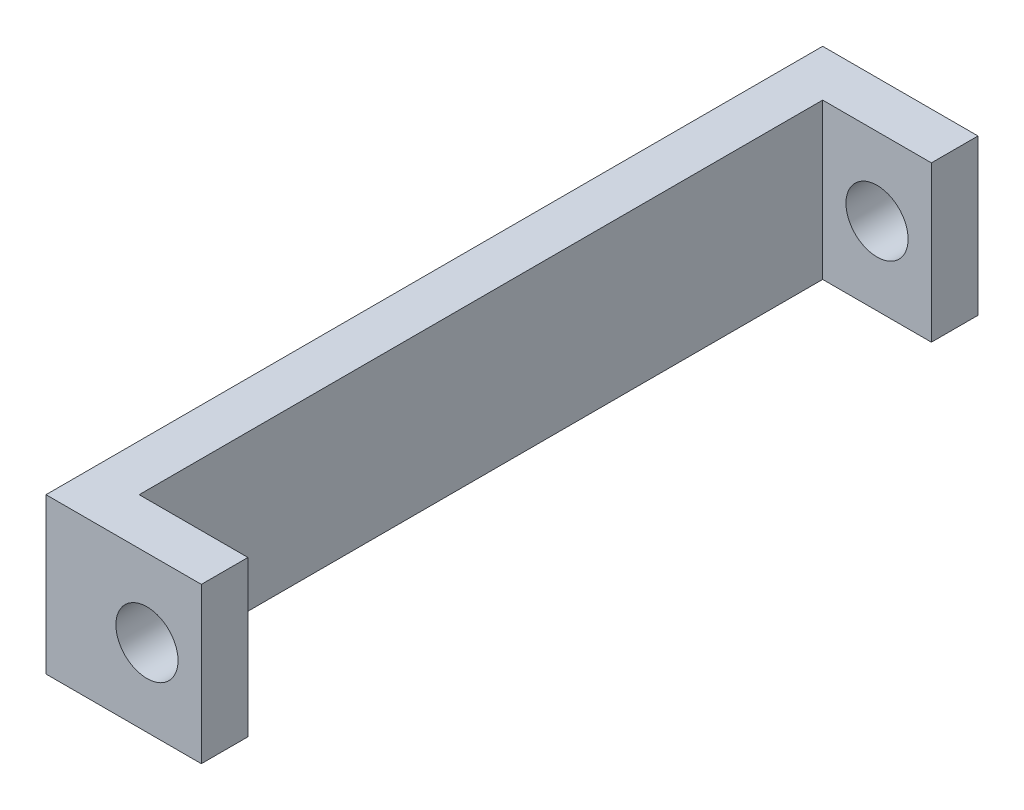
SolidWorks part; units mm, degrees
ref_plane "Front Plane" through (0, 0, 0) normal (0, 0, 1) x (1, 0, 0)
ref_plane "Top Plane" through (0, 0, 0) normal (0, 1, 0) x (1, 0, 0)
ref_plane "Right Plane" through (0, 0, 0) normal (1, 0, 0) x (0, 0, -1)
sketch "Sketch1" plane through (0, 0, 0) normal (0, 0, 1) x (1, 0, 0)
  line L1 (-5, 5) -> (5, 5)
  line L2 (-5, 5) -> (-5, -5)
  line L3 (-5, -5) -> (5, -5)
  line L4 (5, 5) -> (5, -5)
  line L5 (-5, 5) -> (5, -5) construction
  line L6 (-5, -5) -> (5, 5) construction
  point P0 (0, 0)
  dimension "D1" = 10
  dimension "D2" = 10
extrude "Boss-Extrude1" add sketch "Sketch1" along normal blind 50
sketch "Sketch2" plane through (0, 5, 0) normal (0, 1, 0) x (1, 0, 0)
  line L0 (5, -3) -> (5, -47)
  line L1 (5, -3) -> (-2, -3)
  line L2 (5, -47) -> (-2, -47)
  line L3 (-2, -3) -> (-2, -47)
  line L4 (5, -50) -> (5, 0) construction
  line L5 (5, 0) -> (-5, 0) construction
  line L6 (5, -50) -> (-5, -50) construction
  line L7 (-5, -50) -> (-5, 0) construction
  dimension "D1" = 3
  dimension "D2" = 3
  dimension "D3" = 3
extrude "Cut-Extrude1" cut sketch "Sketch2" against normal blind 11
sketch "Sketch3" plane through (0, 0, 50) normal (0, 0, 1) x (1, 0, 0)
  line L1 (0, 0) -> (1.5, 0) construction
  circle A0 centre (1.5, 0) radius 2
  dimension "D2" = 4
  dimension "D1" = 1.5
extrude "Cut-Extrude2" cut sketch "Sketch3" against normal blind 71
